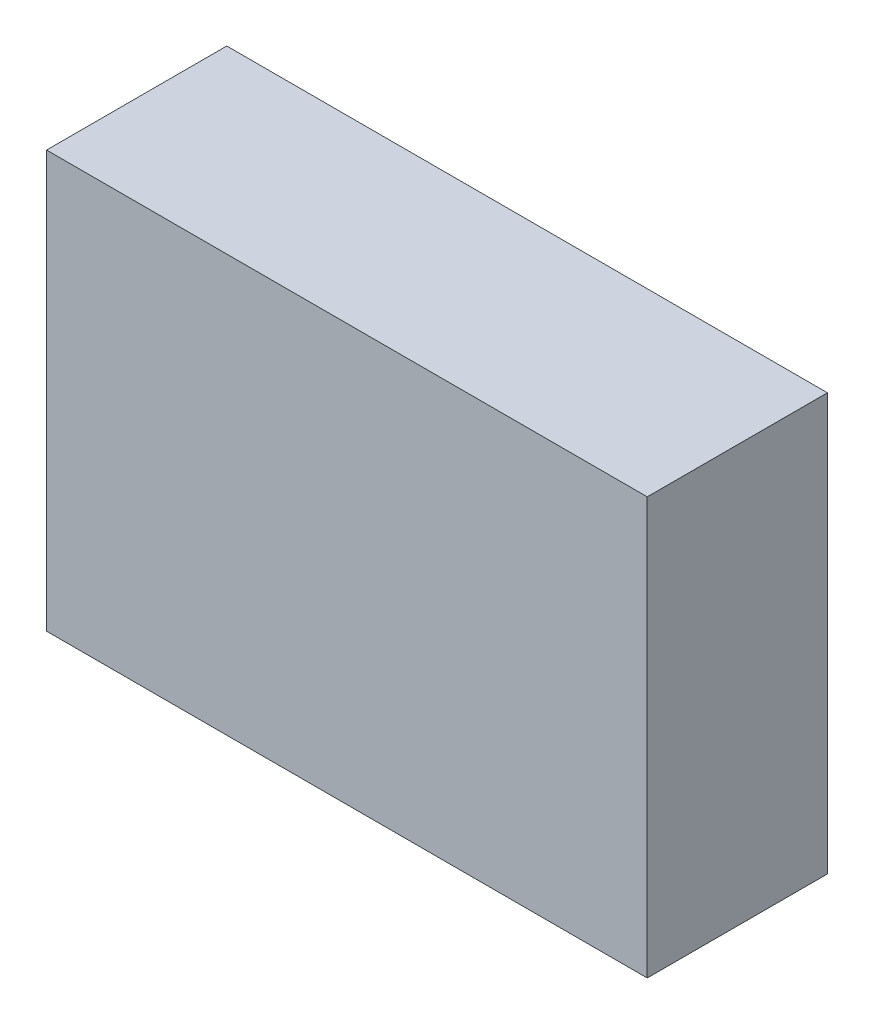
SolidWorks part; units mm, degrees
material "Pine"
ref_plane "Front Plane" through (0, 0, 0) normal (0, 0, 1) x (1, 0, 0)
ref_plane "Top Plane" through (0, 0, 0) normal (0, 1, 0) x (1, 0, 0)
ref_plane "Right Plane" through (0, 0, 0) normal (1, 0, 0) x (0, 0, -1)
sketch "Sketch1" plane through (0, 0, 0) normal (1, 0, 0) x (0, 0, -1)
  line L1 (19.05, -44.0531) -> (-19.05, -44.0531)
  line L2 (19.05, -44.0531) -> (19.05, 44.0531)
  line L3 (19.05, 44.0531) -> (-19.05, 44.0531)
  line L4 (-19.05, -44.0531) -> (-19.05, 44.0531)
  line L5 (19.05, -44.0531) -> (-19.05, 44.0531) construction
  line L6 (19.05, 44.0531) -> (-19.05, -44.0531) construction
  point P0 (0, 0)
  dimension "D1" = 38.1
  dimension "D2" = 88.1063
extrude "Boss-Extrude1" add sketch "Sketch1" along normal blind 127 contours L4 L3 L2 L1
